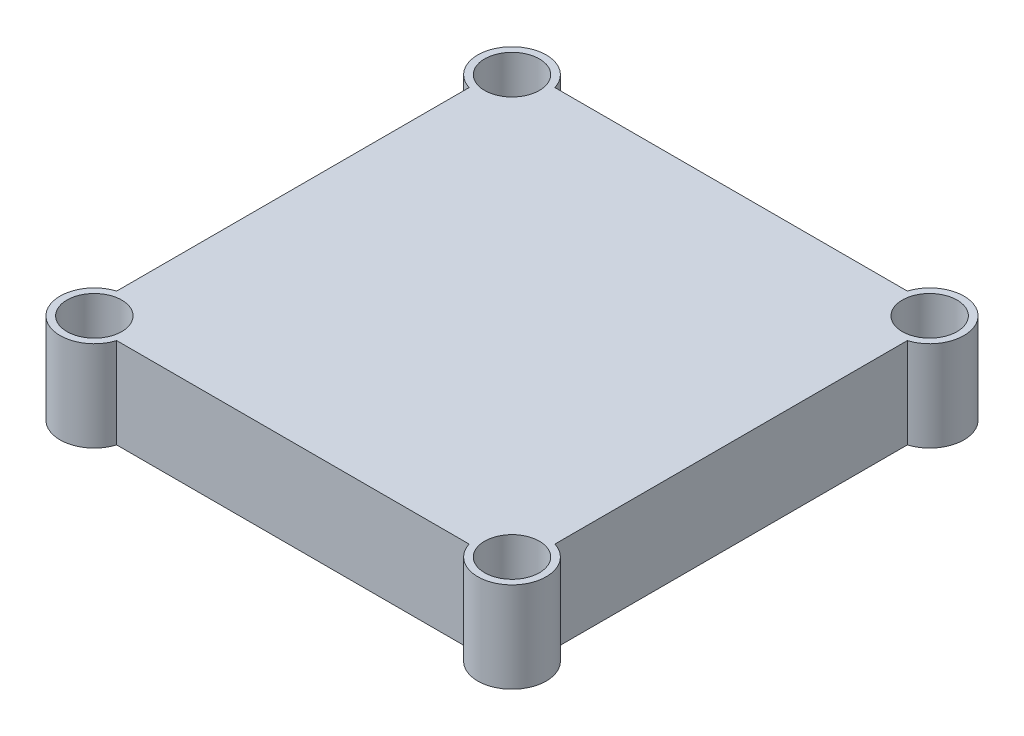
SolidWorks part; units mm, degrees
ref_plane "Front Plane" through (0, 0, 0) normal (0, 0, 1) x (1, 0, 0)
ref_plane "Top Plane" through (0, 0, 0) normal (0, 1, 0) x (1, 0, 0)
ref_plane "Right Plane" through (0, 0, 0) normal (1, 0, 0) x (0, 0, -1)
sketch "Sketch1" plane through (0, 0, 0) normal (0, 1, 0) x (1, 0, 0)
  line L1 (16, -16) -> (-16, -16)
  line L2 (16, -16) -> (16, 16)
  line L3 (16, 16) -> (-16, 16)
  line L4 (-16, -16) -> (-16, 16)
  line L5 (16, -16) -> (-16, 16) construction
  line L6 (16, 16) -> (-16, -16) construction
  line L7 (15.25, -15.25) -> (-15.25, -15.25) construction
  line L8 (15.25, -15.25) -> (15.25, 15.25) construction
  line L9 (15.25, 15.25) -> (-15.25, 15.25) construction
  line L10 (-15.25, -15.25) -> (-15.25, 15.25) construction
  line L11 (15.25, -15.25) -> (-15.25, 15.25) construction
  line L12 (15.25, 15.25) -> (-15.25, -15.25) construction
  circle A0 centre (-15.25, 15.25) radius 2.5
  circle A1 centre (15.25, 15.25) radius 2.5
  circle A2 centre (-15.25, -15.25) radius 2.5
  circle A3 centre (15.25, -15.25) radius 2.5
  point P0 (0, 0)
  point P6 (0, 0)
  dimension "D5" = 5
  dimension "D6" = 5
  dimension "D7" = 5
  dimension "D8" = 5
  dimension "D1" = 32
  dimension "D2" = 32
  dimension "D3" = 30.5
  dimension "D4" = 30.5
extrude "Boss-Extrude1" add sketch "Sketch1" along normal blind 6.6 contours L2 L1 L4 L3 | A2 | A0 | A1 | A3
sketch "Sketch2" plane through (0, 6.6, 0) normal (0, 1, 0) x (1, 0, 0)
  line L1 (-15.25, -15.25) -> (15.25, -15.25) construction
  line L2 (-15.25, -15.25) -> (-15.25, 15.25) construction
  line L3 (-15.25, 15.25) -> (15.25, 15.25) construction
  line L4 (15.25, -15.25) -> (15.25, 15.25) construction
  line L5 (-15.25, -15.25) -> (15.25, 15.25) construction
  line L6 (-15.25, 15.25) -> (15.25, -15.25) construction
  circle A0 centre (-15.25, 15.25) radius 2
  circle A1 centre (15.25, 15.25) radius 2
  circle A2 centre (15.25, -15.25) radius 2
  circle A3 centre (-15.25, -15.25) radius 2
  point P0 (0, 0)
  dimension "D3" = 4
  dimension "D4" = 4
  dimension "D5" = 4
  dimension "D6" = 4
  dimension "D1" = 30.5
  dimension "D2" = 30.5
extrude "Cut-Extrude1" cut sketch "Sketch2" against normal blind 10
